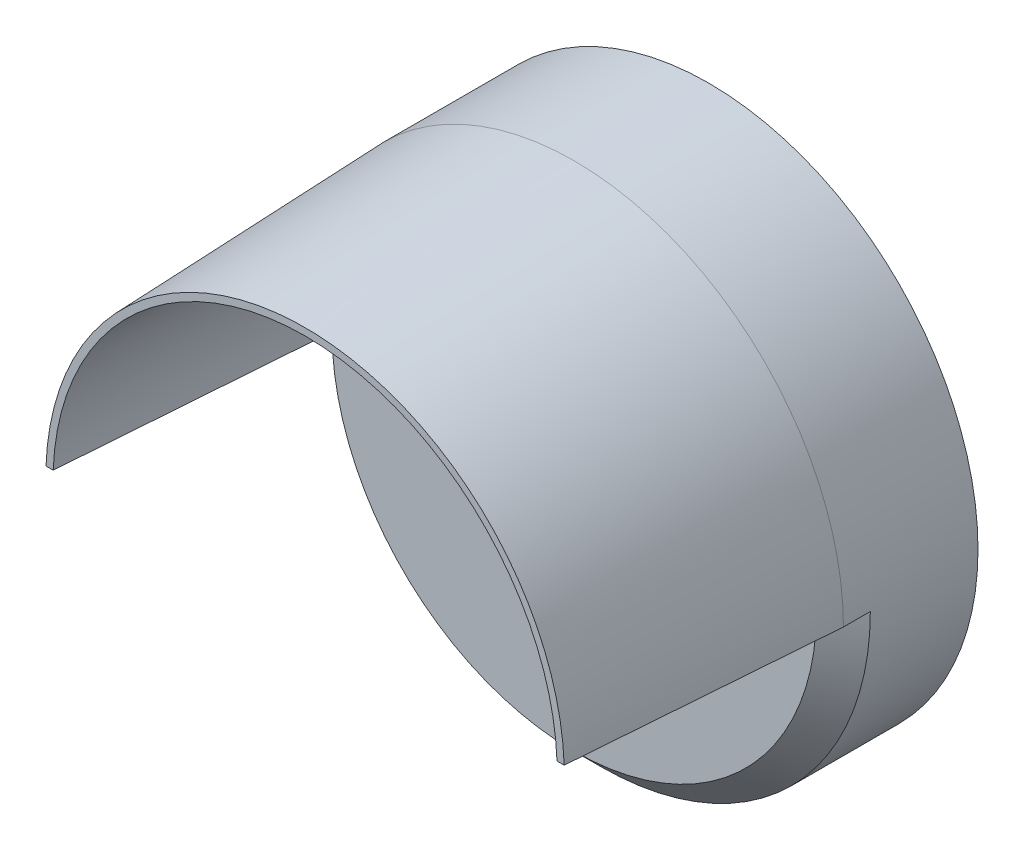
SolidWorks part; units mm, degrees
ref_plane "Front Plane" through (0, 0, 0) normal (0, 0, 1) x (1, 0, 0)
ref_plane "Top Plane" through (0, 0, 0) normal (0, 1, 0) x (1, 0, 0)
ref_plane "Right Plane" through (0, 0, 0) normal (1, 0, 0) x (0, 0, -1)
sketch "Sketch1" plane through (0, 0, 0) normal (0, 0, 1) x (1, 0, 0)
  circle A0 centre (0, 0) radius 25.4
  circle A1 centre (0, 0) radius 9.525
  dimension "D1" = 50.8
  dimension "D2" = 19.05
extrude "Boss-Extrude1" add sketch "Sketch1" along normal blind 12.7
chamfer "Chamfer1" distance 2.54 angle 45 1 edges at (25.4, 0, 12.7)
fillet "Fillet1" radius 1.27 1 edges at (9.525, 0, 12.7)
sketch "Sketch2" plane through (0, 0, 12.7) normal (0, 0, 1) x (1, 0, 0)
  circle A0 centre (0, 0) radius 22.86 construction
  arc A1 (22.86, 0) -> (-22.86, 0) centre (0, 0) ccw
extrude "Extrude-Thin2" add sketch "Sketch2" along normal blind 25.4 draft 2.1 and the other way blind 2.54 thin
